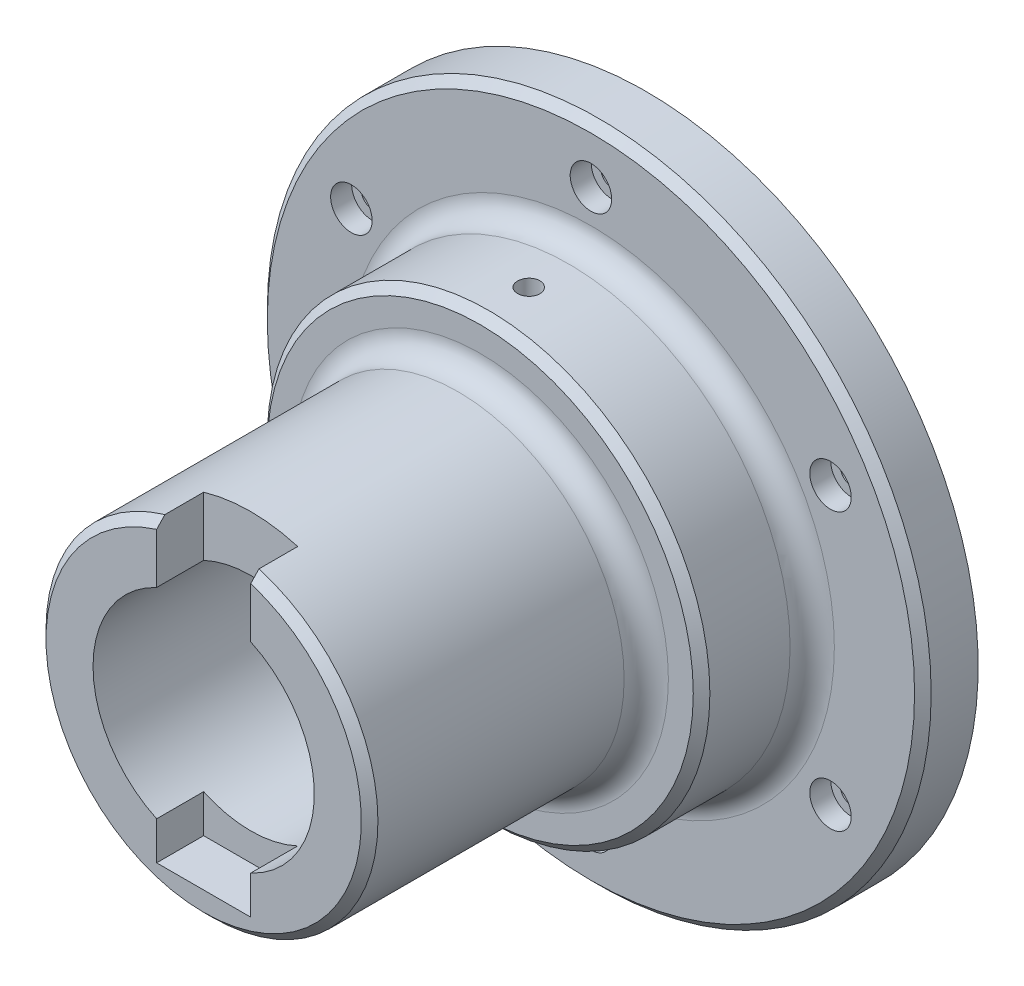
SolidWorks part; units mm, degrees
material "Chrome Stainless Steel"
ref_plane "Front Plane" through (0, 0, 0) normal (0, 0, 1) x (1, 0, 0)
ref_plane "Top Plane" through (0, 0, 0) normal (0, 1, 0) x (1, 0, 0)
ref_plane "Right Plane" through (0, 0, 0) normal (1, 0, 0) x (0, 0, -1)
sketch "Base Sketch" plane through (0, 0, 0) normal (1, 0, 0) x (0, 0, -1)
  line L0 (0, 76.2) -> (-12.7, 76.2)
  line L1 (-12.7, 76.2) -> (-12.7, 50.8)
  line L2 (-12.7, 50.8) -> (-38.1, 50.8)
  line L3 (-38.1, 50.8) -> (-38.1, 38.1)
  line L4 (-38.1, 38.1) -> (-101.6, 38.1)
  line L5 (-101.6, 38.1) -> (-101.6, 25.4)
  line L6 (-101.6, 25.4) -> (-31.75, 25.4)
  line L7 (-31.75, 25.4) -> (-31.75, 28.575)
  line L8 (-31.75, 28.575) -> (-19.05, 28.575)
  line L9 (-19.05, 28.575) -> (-19.05, 25.4)
  line L10 (-19.05, 25.4) -> (0, 25.4)
  line L11 (0, 25.4) -> (0, 76.2)
  line L12 (0, 0) -> (-101.2209, 0) construction
  point P5 (-9.525, 25.4)
  point P13 (-18.7441, 25.4)
  dimension "D1" = 12.7
  dimension "D2" = 12.7
  dimension "D3" = 28.575
  dimension "D4" = 38.1
  dimension "D5" = 101.6
  dimension "D6" = 38.1
  dimension "D7" = 25.4
  dimension "D8" = 25.4
  dimension "D9" = 50.8
  dimension "D10" = 76.2
  dimension "D11" = 19.05
revolve "Base Revolve" add sketch "Base Sketch" angle 360 about L12
fillet "Front Fillet" radius 5.08 2 edges at (-38.1, 0, 38.1) (-50.8, 0, 12.7)
chamfer "Front Chamfer" distance 1.905 angle 45 3 edges at (-76.2, 0, 12.7) (-50.8, 0, 38.1) (-38.1, 0, 101.6)
ref_plane "Forward Plane" through (0, 0, 104.14) normal (0, 0, 1) x (1, 0, 0)
sketch "Block Sketch" plane through (0, 0, 104.14) normal (0, 0, 1) x (1, 0, 0)
  line L0 (0, 0) -> (0, 14.8297) construction
  line L2 (10.795, -31.75) -> (-10.795, -31.75)
  line L3 (10.795, -31.75) -> (10.795, 61.4094)
  line L4 (10.795, 61.4094) -> (-10.795, 61.4094)
  line L5 (-10.795, -31.75) -> (-10.795, 61.4094)
  line L6 (10.795, -31.75) -> (-10.795, 61.4094) construction
  line L7 (10.795, 61.4094) -> (-10.795, -31.75) construction
  dimension "D1" = 31.75
  dimension "D2" = 21.59
  dimension "D3" = 61.4094
extrude "Block Cut" cut sketch "Block Sketch" against normal blind 13.335
sketch "Width Sketch" plane through (0, 0, 0) normal (0, 1, 0) x (1, 0, 0)
  line L0 (50.8, -17.78) -> (-50.8, -17.78) construction
  line L1 (50.8, -36.195) -> (-50.8, -36.195) construction
  line L2 (0, -17.78) -> (0, -36.195) construction
  line L3 (0, -36.195) -> (0, -26.9875) construction
  line L4 (0, -26.9875) -> (-87.4305, -26.9875) construction
  line L5 (-87.4305, -26.9875) -> (107.7657, -26.9875) construction
  point P6 (0, 0)
  point P10 (155.6262, -26.9875)
  point P11 (107.7657, -26.9875)
  dimension "D1" = 195.1962
  dimension "D2" = 76.6355
sketch "Height Sketch" plane through (0, 0, 0) normal (0, 0, 1) x (1, 0, 0)
  line L0 (0, 0) -> (0, 82.3172) construction
ref_plane "Center Plane" through (0, 0, 26.9875) normal (0, 0, 1) x (1, 0, 0)
sketch "Topmost Cut" plane through (0, 0, 26.9875) normal (0, 0, 1) x (1, 0, 0)
  line L0 (0, 0) -> (0, 50.8) construction
  point P9 (0, 50.8)
  dimension "D1" = 50.8
sketch "Circular Sketch" plane through (0, 0, 12.7) normal (0, 0, 1) x (1, 0, 0)
  circle A0 centre (0, 0) radius 63.5 construction
  circle A1 centre (0, 63.5) radius 2.5527
  point P3 (0, 63.5)
  dimension "D1" = 127
  dimension "D2" = 5.1054
extrude "Circular Cut" cut sketch "Circular Sketch" against normal through all
pattern_circular "Circular Pattern" count 6 over 360 about axis through (0, 0, 0) along (0, 0, 1) of "Circular Cut"
sketch "Outer Circular Sketch" plane through (0, 0, 12.7) normal (0, 0, 1) x (1, 0, 0)
  circle A0 centre (0, 63.5) radius 4.7625
  dimension "D1" = 9.525
extrude "Outer Circular Cut" cut sketch "Outer Circular Sketch" against normal blind 4.826
pattern_circular "Outer Circular Pattern" count 6 over 360 about axis through (0, 0, 0) along (0, 0, 1) of "Outer Circular Cut"
hole_wizard "1/4-20 Topmost Cut" positions "3D Sketch" profile "Vertical Sketch" tap size "1/4-20" standard "ANSI Inch"
sketch3d "3D Sketch"
  point P0 (0, 50.8, 26.9875)
sketch "Vertical Sketch" plane through (0, 50.8, 26.9875) normal (1, 0, 0) x (0, 0, 1)
  line L0 (0, 0) -> (0, 22.225)
  line L1 (0, 22.225) -> (2.5527, 22.225)
  line L2 (2.5527, 22.225) -> (2.5527, 0)
  line L5 (2.5527, 0) -> (0, 0)
  line L11 (0, -6.35) -> (0, 107.95) construction
  dimension "Thru Tap Drill Dia." = 5.1054
  dimension "Thru Tap Drill Depth" = 22.225
cosmetic thread "Vertical Hole Thread"
